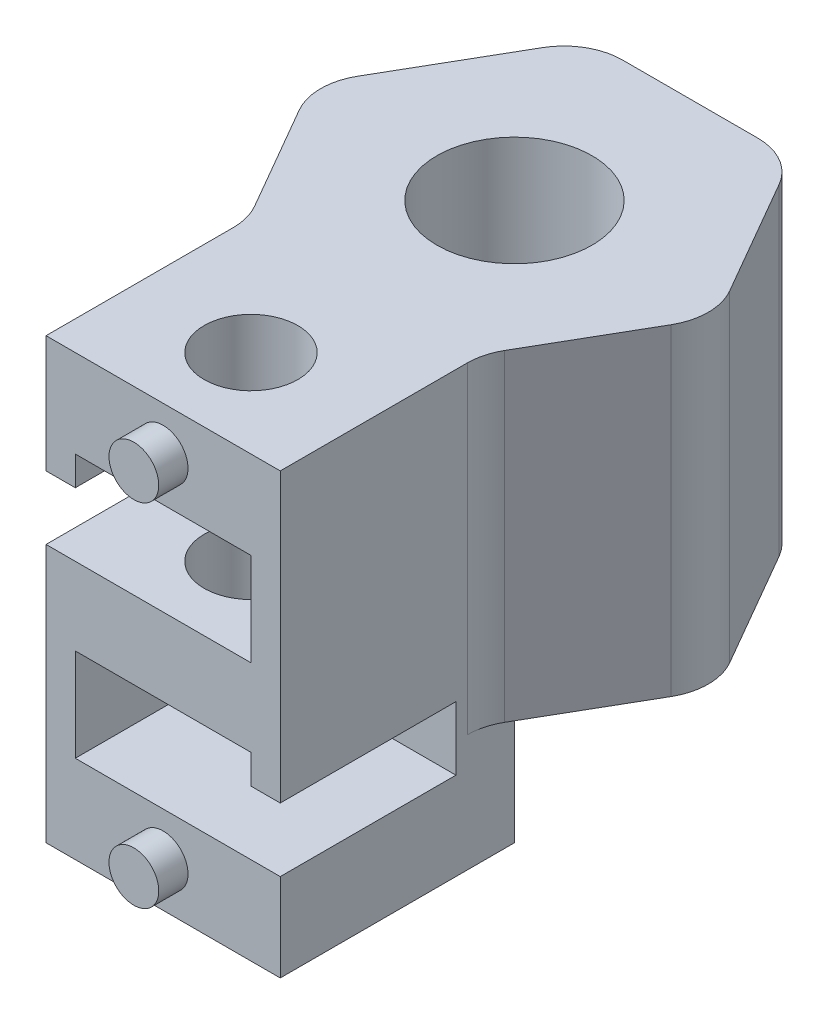
SolidWorks part; units mm, degrees
material "ABS"
ref_plane "Front Plane" through (0, 0, 0) normal (0, 0, 1) x (1, 0, 0)
ref_plane "Top Plane" through (0, 0, 0) normal (0, 1, 0) x (1, 0, 0)
ref_plane "Right Plane" through (0, 0, 0) normal (1, 0, 0) x (0, 0, -1)
sketch "Sketch1" plane through (0, 0, 0) normal (0, 0, 1) x (1, 0, 0)
  line L1 (-4, -7.5) -> (4, -7.5)
  line L2 (-4, -7.5) -> (-4, 7.5)
  line L3 (-4, 7.5) -> (4, 7.5)
  line L4 (4, -7.5) -> (4, 7.5)
  line L5 (-4, -7.5) -> (4, 7.5) construction
  line L6 (-4, 7.5) -> (4, -7.5) construction
  line L7 (-1, -4.5) -> (1, -4.5) construction
  line L8 (-1, -4.5) -> (-1, 4.5) construction
  line L9 (-1, 4.5) -> (1, 4.5) construction
  line L10 (1, -4.5) -> (1, 4.5) construction
  line L11 (-1, -4.5) -> (1, 4.5) construction
  line L12 (-1, 4.5) -> (1, -4.5) construction
  point P0 (0, 0)
  point P6 (0, 0)
  dimension "D1" = 3
  dimension "D2" = 3
  dimension "D3" = 12
  dimension "D4" = 8
extrude "Boss-Extrude1" add sketch "Sketch1" along normal mid plane 8
sketch "Sketch2" plane through (0, 0, 4) normal (0, 0, 1) x (1, 0, 0)
  line L0 (-4, 7.5) -> (-4, -7.5) construction
  line L1 (-3, 4.5) -> (3, 4.5)
  line L2 (-4, 3.5) -> (-4, 1.325)
  line L3 (-4, 1.325) -> (3, 1.325)
  line L4 (3, 4.5) -> (3, 1.325)
  line L5 (4, -7.5) -> (4, 7.5) construction
  line L6 (4, -4.5) -> (-3, -4.5)
  line L7 (4, -4.5) -> (4, -2.325)
  line L8 (3, -1.325) -> (-3, -1.325)
  line L9 (-3, -4.5) -> (-3, -1.325)
  line L10 (0, 0) -> (-4, 0) construction
  line L11 (4, 7.5) -> (-4, 7.5) construction
  line L13 (4, -2.325) -> (3, -2.325)
  line L14 (3, -2.325) -> (3, -1.325)
  line L15 (-4, 3.5) -> (-3, 3.5)
  line L16 (-3, 3.5) -> (-3, 4.5)
  point P0 (-3.0514, 1.325)
  dimension "D1" = 3.175
  dimension "D2" = 3
  dimension "D3" = 3.175
  dimension "D6" = 1
  dimension "D7" = 1
  dimension "D5" = 7
  dimension "D8" = 1
  dimension "D9" = 1
  dimension "D4" = 7
extrude "Cut-Extrude1" cut sketch "Sketch2" against normal blind 6
sketch "Sketch6" plane through (0, 7.5, 0) normal (0, 1, 0) x (1, 0, 0)
  line L0 (4, -4) -> (-4, -4) construction
  point P0 (0, -1)
  dimension "D1" = 3
hole_wizard "M3 Clearance Hole2" positions "Sketch7" profile "Sketch8" hole size "M3" standard "ANSI Metric"
sketch "Sketch7" plane through (0, 7.5, 0) normal (0, 1, 0) x (1, 0, 0)
  point P0 (0, -1)
sketch "Sketch8" plane through (0, 7.5, 1) normal (1, 0, 0) x (0, 0, 1)
  line L0 (0, 0) -> (0, 12.9614)
  line L1 (0, 12.9614) -> (1.6, 12)
  line L2 (1.6, 12) -> (1.6, 0)
  line L5 (1.6, 0) -> (0, 0)
  line L10 (0, 12.9614) -> (-1.6, 12) construction
  line L11 (0, -6.35) -> (0, 107.95) construction
  dimension "Hole Dia." = 3.2
  dimension "Hole Depth" = 12
  dimension "Drill Angle" = 118
sketch "Sketch9" plane through (0, 0, 4) normal (0, 0, 1) x (1, 0, 0)
  line L0 (4, 7.5) -> (-4, 7.5) construction
  line L3 (0, 0) -> (4, 0) construction
  line L4 (4, -2.325) -> (4, 7.5) construction
  circle A0 centre (0, 6) radius 0.85
  circle A1 centre (0, -6) radius 0.85
  dimension "D1" = 1.7
  dimension "D2" = 1.5
extrude "Boss-Extrude2" add sketch "Sketch9" along normal blind 1
sketch "Sketch12" plane through (0, 0, -4) normal (0, 0, -1) x (-1, 0, 0)
  line L0 (4, 7.5) -> (4, -7.5) construction
  line L1 (-4, 7.5) -> (4, 7.5)
  line L2 (-4, 7.5) -> (-4, 1.5)
  line L3 (-4, 1.5) -> (4, 1.5)
  line L4 (4, 7.5) -> (4, 1.5)
  dimension "D1" = 6
extrude "Boss-Extrude3" add sketch "Sketch12" along normal blind 8
sketch "Sketch13" plane through (0, 7.5, 0) normal (0, 1, 0) x (1, 0, 0)
  line L0 (-4, 12) -> (4, 12) construction
  point P0 (0, 8)
  dimension "D1" = 4
hole_wizard "M5 Clearance Hole1" positions "Sketch14" profile "Sketch15" hole size "M5" standard "ANSI Metric" end condition through all
sketch "Sketch14" plane through (0, 7.5, 0) normal (0, 1, 0) x (1, 0, 0)
  point P0 (0, 8)
sketch "Sketch15" plane through (0, 7.5, -8) normal (1, 0, 0) x (0, 0, 1)
  line L0 (0, 0) -> (0, 15)
  line L1 (0, 15) -> (2.65, 15)
  line L2 (2.65, 15) -> (2.65, 0)
  line L5 (2.65, 0) -> (0, 0)
  line L11 (0, -6.35) -> (0, 107.95) construction
  dimension "Thru Hole Dia." = 5.3
  dimension "Thru Hole Depth" = 15
sketch "Sketch18" plane through (0, 7.5, 0) normal (0, 1, 0) x (1, 0, 0)
  line L1 (4.6188, 8) -> (2.3094, 12)
  line L2 (2.3094, 12) -> (-2.3094, 12)
  line L3 (-2.3094, 12) -> (-4.6188, 8)
  line L4 (-4.6188, 8) -> (-2.3094, 4)
  line L5 (-2.3094, 4) -> (2.3094, 4)
  line L6 (2.3094, 4) -> (4.6188, 8)
  circle A0 centre (0, 8) radius 4 construction
  circle A1 centre (0, 8) radius 2.65 construction
  circle A2 centre (0, 8) radius 2.65
  dimension "D1" = 8
extrude "Boss-Extrude4" add sketch "Sketch18" against normal up to surface (6 mm away) up to face at (0, 1.5, -5.35)
sketch "Sketch19" plane through (0, 7.5, 0) normal (0, 1, 0) x (1, 0, 0)
  line L1 (6.9282, 8) -> (3.4641, 14)
  line L2 (3.4641, 14) -> (-3.4641, 14)
  line L3 (-3.4641, 14) -> (-6.9282, 8)
  line L4 (-6.9282, 8) -> (-3.4641, 2)
  line L5 (-3.4641, 2) -> (3.4641, 2)
  line L6 (3.4641, 2) -> (6.9282, 8)
  line L7 (4.6188, 8) -> (2.3094, 12)
  line L8 (2.3094, 12) -> (-2.3094, 12)
  line L9 (-2.3094, 12) -> (-4.6188, 8)
  line L10 (-4.6188, 8) -> (-2.3094, 4)
  line L11 (-2.3094, 4) -> (2.3094, 4)
  line L12 (2.3094, 4) -> (4.6188, 8)
  circle A0 centre (0, 8) radius 6 construction
  circle A1 centre (0, 8) radius 4 construction
  circle A2 centre (0, 8) radius 2.65 construction
  circle A3 centre (0, 8) radius 2.65
  point P1 (5.3203, 8)
  line M13 (-4.6188, 8) -> (-4, 6.9282)
  line M14 (-4, 6.9282) -> (-4, -4)
  line M16 (4, -4) -> (4, 6.9282)
  line M17 (4, 6.9282) -> (4.6188, 8)
  line M18 (4.6188, 8) -> (4, 9.0718)
  line M19 (4, 9.0718) -> (4, 12)
  line M20 (4, 12) -> (-4, 12)
  line M21 (-4, 12) -> (-4, 9.0718)
  line M22 (-4, 9.0718) -> (-4.6188, 8)
  dimension "D1" = 12
extrude "Boss-Extrude5" add sketch "Sketch19" against normal offset from surface (11 mm away) 5 contours L6 L1 L2 L3 L4 M16 M14 M13 M22 M21 M20 M19 M18 M17 | L7 M19 M20 | L9 M20 M21 | L12 L11 L10 L4 L5 L6 M14 M16 up to face at (0, 1.5, -8) offset beyond the face yes
fillet "Fillet2" radius 2 6 edges at (-6.9282, 2, -8) (-3.4641, 2, -14) (3.4641, 2, -14) (6.9282, 2, -8) (4, 2, -2.9282) (-4, 2, -2.9282)
equation "\"D1@Boss-Extrude1\"=0.5in"
equation "\"D1@Sketch2\"=0.125in"
equation "\"D3@Sketch2\"=0.125in"
